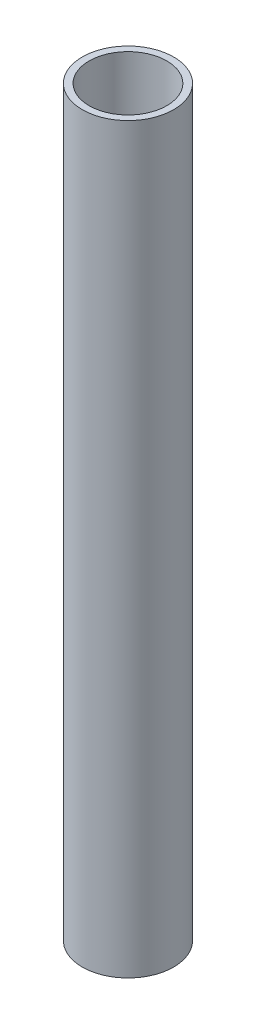
SolidWorks part; units mm, degrees
ref_plane "前视基准面" through (0, 0, 0) normal (0, 0, 1) x (1, 0, 0)
ref_plane "上视基准面" through (0, 0, 0) normal (0, 1, 0) x (1, 0, 0)
ref_plane "右视基准面" through (0, 0, 0) normal (1, 0, 0) x (0, 0, -1)
other "Configuration Table"
sketch "草图1" plane through (0, 0, 0) normal (0, 1, 0) x (1, 0, 0)
  circle A14 centre (0, 0) radius 16
  circle A15 centre (0, 0) radius 13.6
  dimension "D1" = 32
  dimension "D2" = 2.4
extrude "凸台-拉伸1" add sketch "草图1" along normal blind 260
